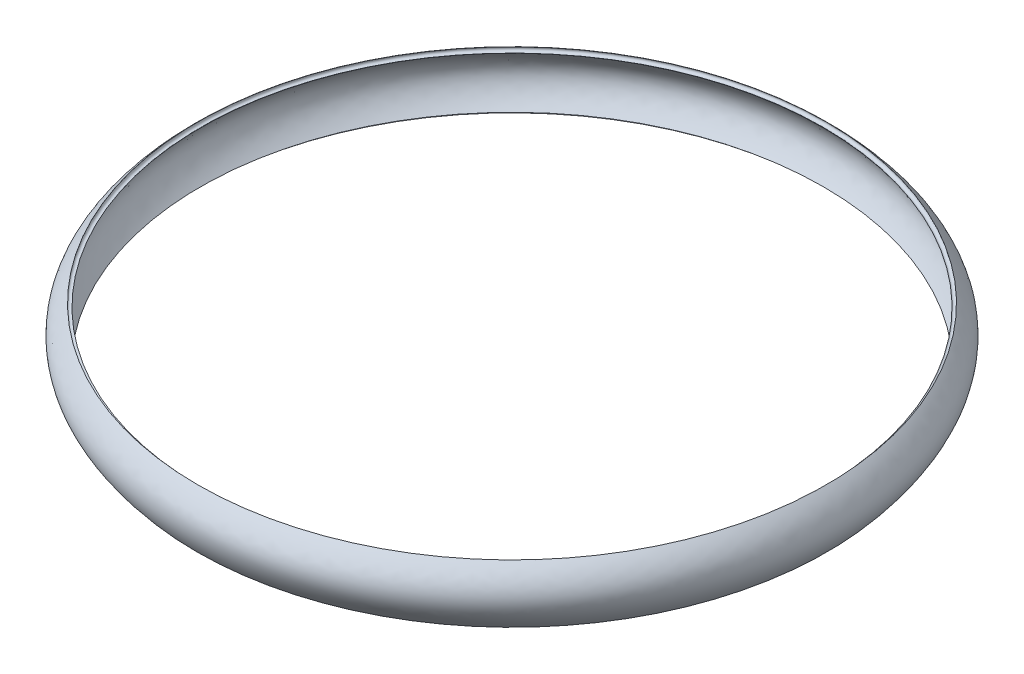
SolidWorks part; units mm, degrees
ref_plane "Front Plane" through (0, 0, 0) normal (0, 0, 1) x (1, 0, 0)
ref_plane "Top Plane" through (0, 0, 0) normal (0, 1, 0) x (1, 0, 0)
ref_plane "Right Plane" through (0, 0, 0) normal (1, 0, 0) x (0, 0, -1)
sketch "Sketch6" plane through (0, 0, 0) normal (0, 0, 1) x (1, 0, 0)
  line L0 (-67.0471, 5.5401) -> (-67.116, -5.5401) construction
  line L2 (0, 3.2925) -> (0, -2.5513) construction
  arc A1 (-67.8772, -6.1886) -> (-67.116, -5.5401) centre (-67.4966, -5.8644) cw
  arc A2 (-67.7245, 6.2757) -> (-67.0471, 5.5401) centre (-67.3858, 5.9079) ccw
  spline S0 degree 3 poles (-67.7245, 6.2757) (-72.29, 2.0716) (-71.851, -1.5246) (-67.8772, -6.1886) knots 0 0 0 0 0.748104 0.748104 0.748104 0.748104
  spline S2 degree 1 poles (-67.0471, 5.5401) (-67.116, -5.5401) knots 0 0 1 1 construction
  spline S3 degree 3 poles (-67.0471, 5.5401) (-67.3051, 5.3025) (-67.8245, 4.7945) (-68.6575, 3.8526) (-69.4237, 2.7203) (-69.9168, 1.4591) (-70.0577, 0.2416) (-69.872, -1.0229) (-69.3391, -2.3964) (-68.5854, -3.6488) (-67.8097, -4.7027) (-67.3469, -5.2692) (-67.116, -5.5401) knots 0 0 0 0 0.046756 0.093513 0.187026 0.280539 0.374052 0.467565 0.561078 0.654591 0.701347 0.748104 0.748104 0.748104 0.748104
  dimension "D1" = 1
revolve "Revolve3" add sketch "Sketch6" angle 360 about L2
